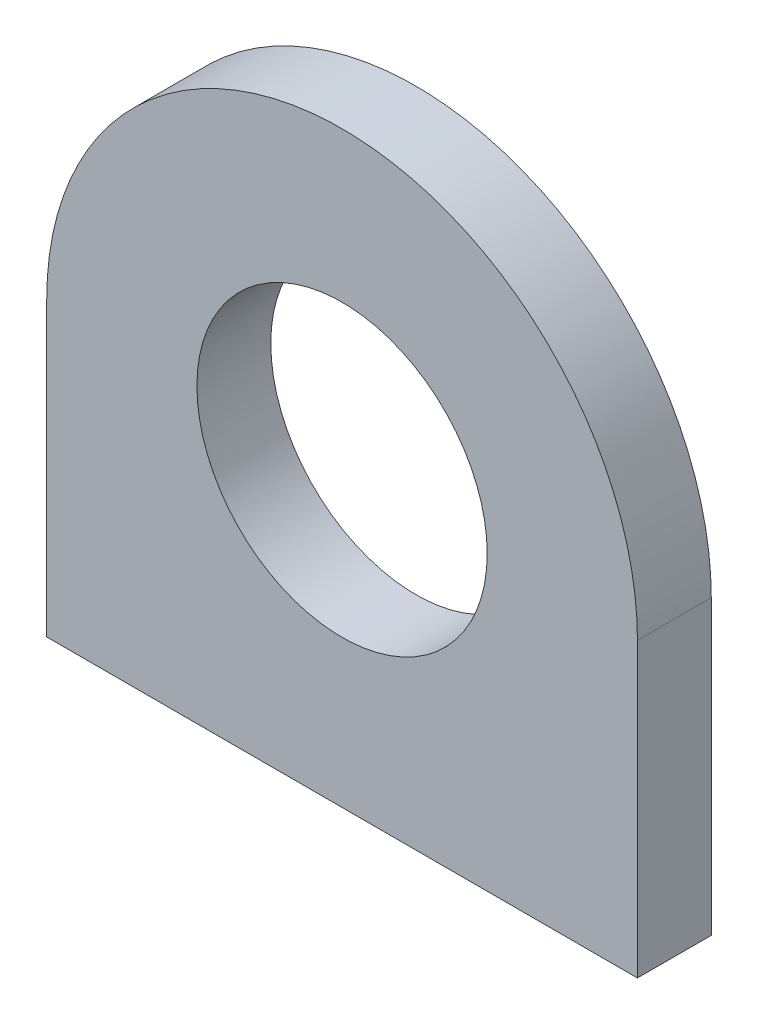
SolidWorks part; units mm, degrees
ref_plane "Front Plane" through (0, 0, 0) normal (0, 0, 1) x (1, 0, 0)
ref_plane "Top Plane" through (0, 0, 0) normal (0, 1, 0) x (1, 0, 0)
ref_plane "Right Plane" through (0, 0, 0) normal (1, 0, 0) x (0, 0, -1)
sketch "Sketch1" plane through (0, 0, 0) normal (0, 0, 1) x (1, 0, 0)
  line L0 (-12.7, 0) -> (-12.7, -12.5751)
  line L1 (-12.7, -12.5751) -> (12.7, -12.5751)
  line L2 (12.7, -12.5751) -> (12.7, 0)
  arc A0 (12.7, 0) -> (-12.7, 0) centre (0, 0) ccw
  circle A1 centre (0, 0) radius 6.2411
extrude "Boss-Extrude1" add sketch "Sketch1" along normal blind 3.175
